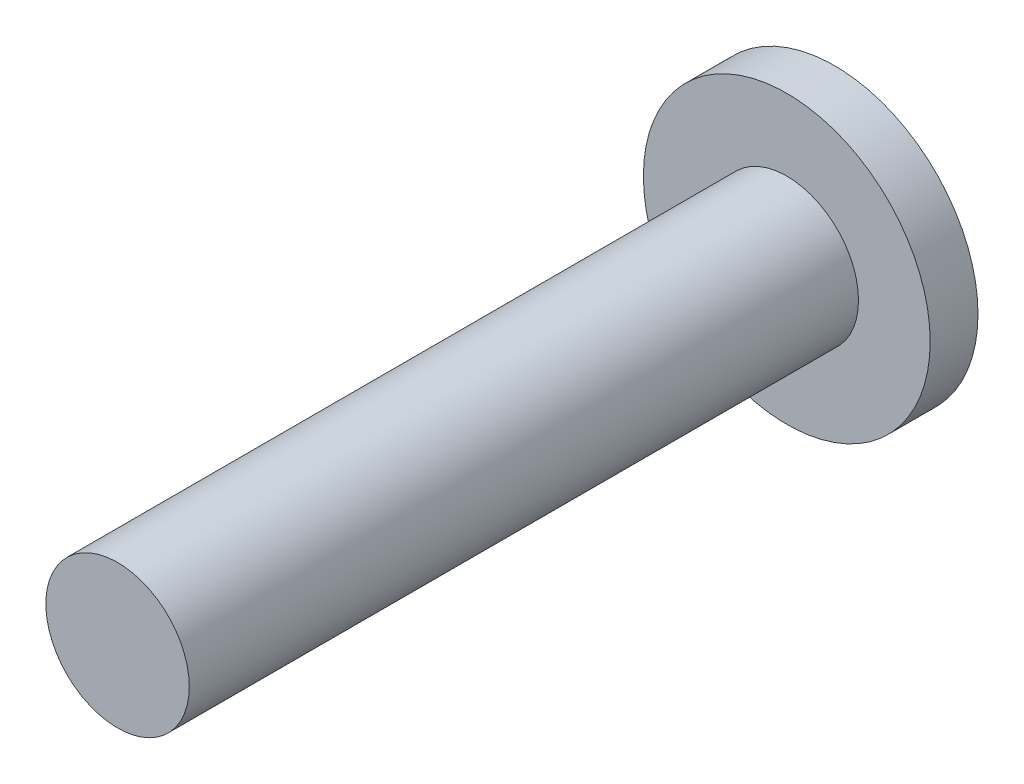
SolidWorks part; units mm, degrees
ref_plane "前视基准面" through (0, 0, 0) normal (0, 0, 1) x (1, 0, 0)
ref_plane "上视基准面" through (0, 0, 0) normal (0, 1, 0) x (1, 0, 0)
ref_plane "右视基准面" through (0, 0, 0) normal (1, 0, 0) x (0, 0, -1)
sketch "草图1" plane through (0, 0, 0) normal (0, 0, 1) x (1, 0, 0)
  circle A0 centre (0, 0) radius 3
extrude "凸台-拉伸1" add sketch "草图1" along normal blind 1
sketch "草图2" plane through (0, 0, 1) normal (0, 0, 1) x (1, 0, 0)
  circle A0 centre (0, 0) radius 1.5
extrude "凸台-拉伸2" add sketch "草图2" along normal blind 14
